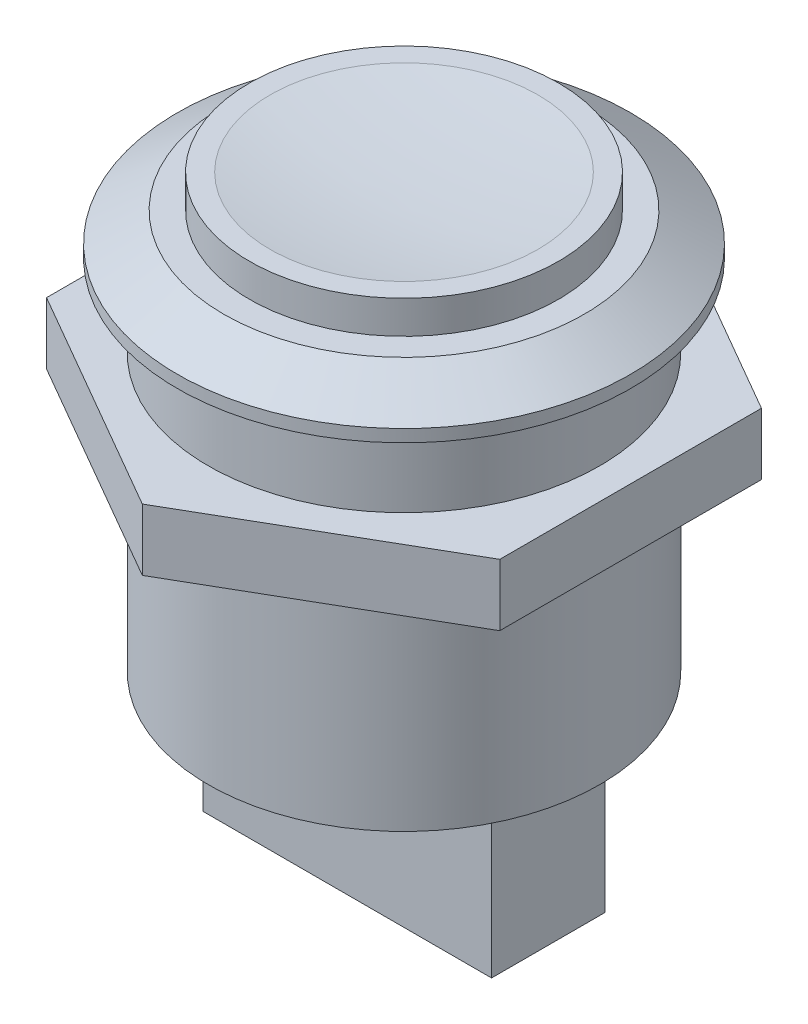
SolidWorks part; units mm, degrees
ref_plane "Front Plane" through (0, 0, 0) normal (0, 0, 1) x (1, 0, 0)
ref_plane "Top Plane" through (0, 0, 0) normal (0, 1, 0) x (1, 0, 0)
ref_plane "Right Plane" through (0, 0, 0) normal (1, 0, 0) x (0, 0, -1)
sketch "Sketch1" plane through (0, 0, 0) normal (0, 0, 1) x (1, 0, 0)
  line L0 (9.5, 0) -> (11, 0)
  line L2 (8.75, 2) -> (7.5, 2)
  line L3 (7.5, 2) -> (7.5, 3.6)
  line L4 (7.5, 3.6) -> (6.5, 3.6)
  line L5 (0, 3.1) -> (0, -17.4)
  line L6 (0, -17.4) -> (9.5, -17.4)
  line L7 (9.5, -17.4) -> (9.5, 0)
  line L8 (0, 3.6) -> (0, 8.2409) construction
  line L9 (11, 0) -> (11, 0.6)
  line L10 (11, 0.6) -> (8.75, 2)
  arc A0 (6.5, 3.6) -> (0, 3.1) centre (0, 45.6) cw
  point P10 (10.25, 0)
  point P15 (0, 0)
  point P16 (0, 2.8041)
  point P17 (0, 0)
  dimension "D1" = 3.6
  dimension "D2" = 15
  dimension "D3" = 22
  dimension "D4" = 19
  dimension "D5" = 2
  dimension "D6" = 17.5
  dimension "D7" = 0.6
  dimension "D8" = 21
  dimension "D9" = 0.5
  dimension "D10" = 1
revolve "Revolve1" add sketch "Sketch1" angle 360 about L8
sketch "Sketch2" plane through (0, -17.4, 0) normal (0, -1, 0) x (1, 0, 0)
  line L1 (-7, 2.75) -> (7, 2.75)
  line L2 (-7, 2.75) -> (-7, -2.75)
  line L3 (-7, -2.75) -> (7, -2.75)
  line L4 (7, 2.75) -> (7, -2.75)
  line L5 (-7, 2.75) -> (7, -2.75) construction
  line L6 (-7, -2.75) -> (7, 2.75) construction
  point P0 (0, 0)
  dimension "D1" = 14
  dimension "D2" = 5.5
extrude "Boss-Extrude1" add sketch "Sketch2" along normal blind 8
sketch "Sketch3" plane through (0, 0, 0) normal (0, -1, 0) x (1, 0, 0)
  line L1 (0, 12.7017) -> (-11, 6.3509)
  line L2 (-11, 6.3509) -> (-11, -6.3509)
  line L3 (-11, -6.3509) -> (0, -12.7017)
  line L4 (0, -12.7017) -> (11, -6.3509)
  line L5 (11, -6.3509) -> (11, 6.3509)
  line L6 (11, 6.3509) -> (0, 12.7017)
  circle A0 centre (0, 0) radius 11 construction
  dimension "D1" = 22
extrude "Boss-Extrude2" add sketch "Sketch3" along normal blind 3 from offset 4
